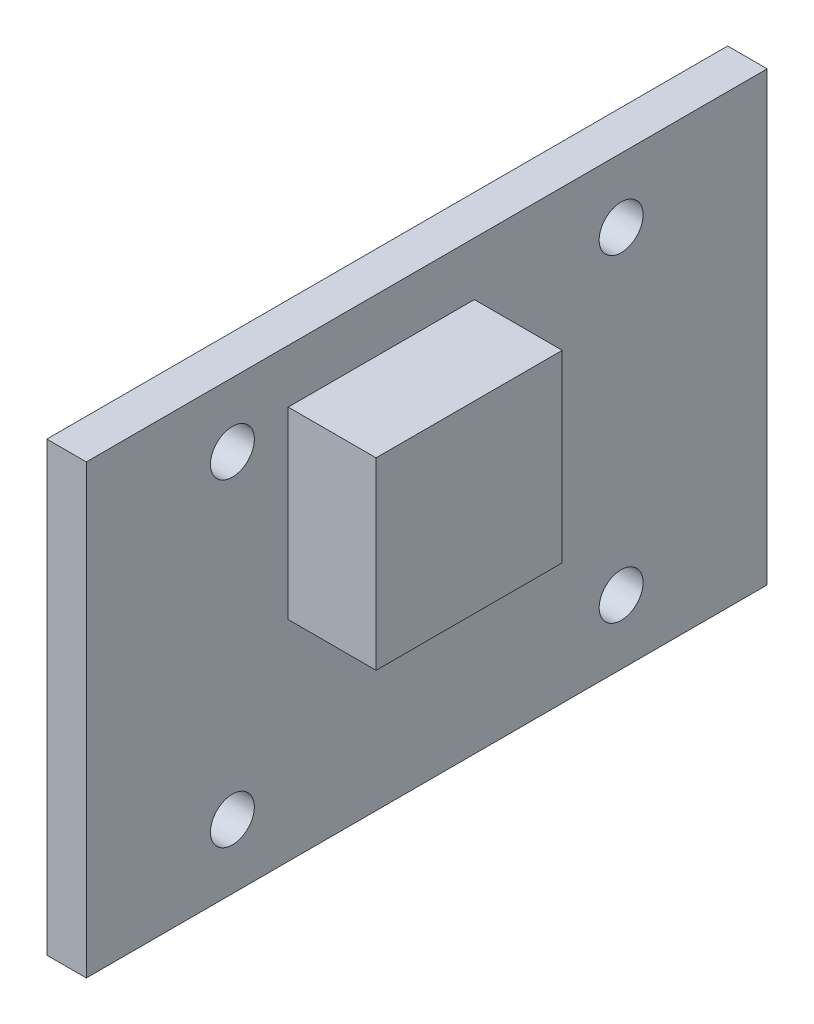
SolidWorks part; units mm, degrees
ref_plane "Front Plane" through (0, 0, 0) normal (0, 0, 1) x (1, 0, 0)
ref_plane "Top Plane" through (0, 0, 0) normal (0, 1, 0) x (1, 0, 0)
ref_plane "Right Plane" through (0, 0, 0) normal (1, 0, 0) x (0, 0, -1)
sketch "Sketch1" plane through (0, 0, 0) normal (1, 0, 0) x (0, 0, -1)
  line L0 (0, 10.175) -> (31, 10.175) construction
  line L1 (0, 0) -> (31, 0)
  line L2 (0, 0) -> (0, 20.35)
  line L3 (0, 20.35) -> (31, 20.35)
  line L4 (31, 0) -> (31, 20.35)
  line L6 (15.5, 20.35) -> (15.5, 0) construction
  circle A0 centre (6.65, 2.925) radius 1
  circle A1 centre (6.65, 17.425) radius 1
  circle A2 centre (24.35, 17.425) radius 1
  circle A3 centre (24.35, 2.925) radius 1
  dimension "D5" = 2
  dimension "D1" = 20.35
  dimension "D2" = 31
  dimension "D3" = 17.7
  dimension "D4" = 14.5
extrude "Boss-Extrude1" add sketch "Sketch1" along normal blind 1.8
sketch "Sketch2" plane through (1.8, 0, 0) normal (1, 0, 0) x (0, 0, -1)
  line L1 (9.1914, 17.9161) -> (17.6681, 17.9161)
  line L2 (9.1914, 17.9161) -> (9.1914, 9.5373)
  line L3 (9.1914, 9.5373) -> (17.6681, 9.5373)
  line L4 (17.6681, 17.9161) -> (17.6681, 9.5373)
extrude "Boss-Extrude2" add sketch "Sketch2" along normal blind 4
